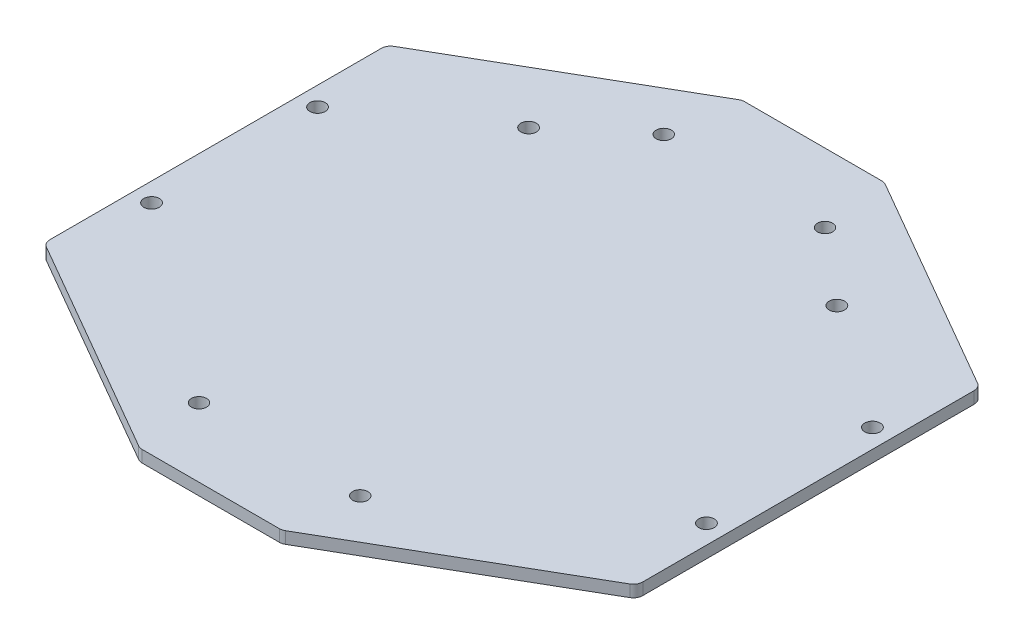
SolidWorks part; units mm, degrees
ref_plane "Front Plane" through (0, 0, 0) normal (0, 0, 1) x (1, 0, 0)
ref_plane "Top Plane" through (0, 0, 0) normal (0, 1, 0) x (1, 0, 0)
ref_plane "Right Plane" through (0, 0, 0) normal (1, 0, 0) x (0, 0, -1)
sketch "Sketch1" plane through (0, 0, 0) normal (0, 1, 0) x (1, 0, 0)
  line L0 (-15, 63.5085) -> (15, 63.5085)
  line L1 (-15, 63.5085) -> (-62.5, 36.0844)
  line L2 (-62.5, 36.0844) -> (-62.5, -36.0844)
  line L3 (-62.5, -36.0844) -> (-15, -63.5085)
  line L4 (15, -63.5085) -> (62.5, -36.0844)
  line L5 (62.5, -36.0844) -> (62.5, 36.0844)
  line L6 (62.5, 36.0844) -> (15, 63.5085)
  line L7 (-15, -63.5085) -> (15, -63.5085)
  line L8 (15, 63.5085) -> (0, 72.1688) construction
  line L9 (0, 72.1688) -> (-15, 63.5085) construction
  line L10 (-15, -63.5085) -> (0, -72.1688) construction
  line L11 (0, -72.1688) -> (15, -63.5085) construction
  circle A0 centre (0, 0) radius 62.5 construction
  dimension "D1" = 125
  dimension "D2" = 30
  dimension "D3" = 30
extrude "Boss-Extrude1" add sketch "Sketch1" along normal blind 2.5
sketch "Sketch3" plane through (0, 0, 0) normal (0, -1, 0) x (1, 0, 0)
  line L0 (-17, 49) -> (17, 49) construction
  line L1 (0, 0) -> (62.5, 0) construction
  line L3 (62.5, 36.0844) -> (62.5, -36.0844) construction
  line L4 (-17, -49) -> (17, -49) construction
  circle A0 centre (17, 49) radius 1.6
  circle A1 centre (-17, 49) radius 1.6
  circle A4 centre (17, -49) radius 1.6
  circle A5 centre (-17, -49) radius 1.6
  point P4 (0, 49)
  dimension "D1" = 3.2
  dimension "D2" = 3.2
  dimension "D3" = 34
  dimension "D4" = 49
extrude "Cut-Extrude1" cut sketch "Sketch3" against normal blind 10
sketch "Sketch5" plane through (0, 2.5, 0) normal (0, 1, 0) x (1, 0, 0)
  line L0 (32.5, 36) -> (-32.5, 36) construction
  circle A0 centre (-32.5, 36) radius 1.625
  circle A1 centre (32.5, 36) radius 1.625
  point P4 (0, 36)
  dimension "D1" = 3.25
  dimension "D2" = 3.25
  dimension "D3" = 65
  dimension "D4" = 36
extrude "Cut-Extrude2" cut sketch "Sketch5" against normal blind 10
sketch "Sketch6" plane through (0, 2.5, 0) normal (0, 1, 0) x (1, 0, 0)
  line L0 (-62.5, 36.0844) -> (-62.5, -36.0844) construction
  line L1 (-58.5, 17.5) -> (-58.5, -17.5) construction
  line L2 (0, 0) -> (0, -63.5085) construction
  line L3 (-15, -63.5085) -> (15, -63.5085) construction
  line L4 (58.5, 17.5) -> (58.5, -17.5) construction
  circle A0 centre (-58.5, 17.5) radius 1.625
  circle A1 centre (-58.5, -17.5) radius 1.625
  circle A2 centre (58.5, -17.5) radius 1.625
  circle A3 centre (58.5, 17.5) radius 1.625
  point P6 (-58.5, 0)
  dimension "D1" = 3.25
  dimension "D2" = 3.25
  dimension "D3" = 4
  dimension "D4" = 35
extrude "Cut-Extrude3" cut sketch "Sketch6" against normal through all both and the other way through all
fillet "Fillet1" radius 2 8 edges at (15, 1.25, -63.5085) (-15, 1.25, -63.5085) (-62.5, 1.25, -36.0844) (-62.5, 1.25, 36.0844) (-15, 1.25, 63.5085) (15, 1.25, 63.5085) (62.5, 1.25, 36.0844) (62.5, 1.25, -36.0844)
